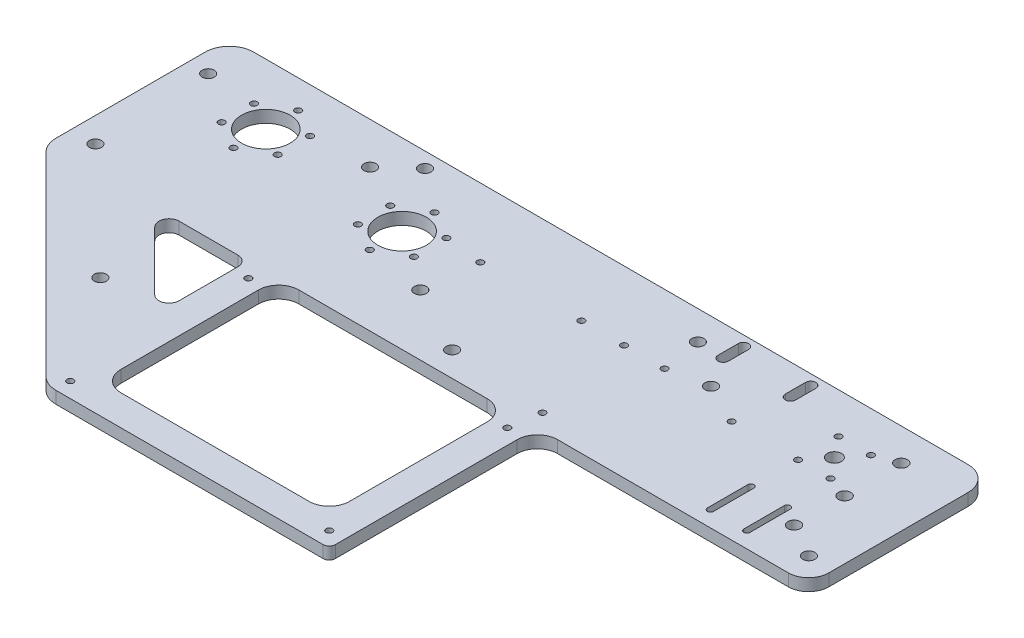
SolidWorks part; units mm, degrees
material "Policarbonato"
ref_plane "Plano frontal" through (0, 0, 0) normal (0, 0, 1) x (1, 0, 0)
ref_plane "Plano superior" through (0, 0, 0) normal (0, 1, 0) x (1, 0, 0)
ref_plane "Plano direito" through (0, 0, 0) normal (1, 0, 0) x (0, 0, -1)
sketch "Esboço1" plane through (0, 0, 0) normal (0, 1, 0) x (1, 0, 0)
  line L3 (-80.5574, -153.6487) -> (51.4721, -153.6487)
  line L4 (54.4721, -150.6487) -> (54.4721, -60.7886)
  line L6 (188.5279, -40.7886) -> (188.5279, 28)
  line L7 (176.5279, 40) -> (-176.5279, 40)
  line L8 (-188.5279, 28) -> (-188.5279, -45.6781)
  line L12 (-122.5768, -50.7886) -> (-93.5279, -50.7886)
  line L13 (-88.5279, -55.7886) -> (-88.5279, -84.8375)
  line L14 (-97.0635, -88.373) -> (-126.1124, -59.3241)
  line L15 (39.4721, -60.6487) -> (39.4721, -128.6487)
  line L16 (29.4721, -138.6487) -> (-63.5279, -138.6487)
  line L17 (-73.5279, -128.6487) -> (-73.5279, -60.6487)
  line L18 (-63.5279, -50.6487) -> (29.4721, -50.6487)
  line L20 (132.5279, 0) -> (148.5279, 0) construction
  line L21 (132.5279, 0) -> (132.5279, 20) construction
  line L22 (132.5279, 20) -> (148.5279, 20) construction
  line L23 (148.5279, 0) -> (148.5279, 20) construction
  line L24 (132.5279, 0) -> (148.5279, 20) construction
  line L25 (132.5279, 20) -> (148.5279, 0) construction
  line L30 (64.4721, -50.7886) -> (178.5279, -50.7886)
  line L31 (150.2221, -43) -> (150.2221, -23) construction
  line L32 (148.7221, -43) -> (148.7221, -23)
  line L33 (151.7221, -43) -> (151.7221, -23)
  line L34 (141.2221, -45.2211) -> (141.2221, -21.4375) construction
  line L36 (132.2221, -43) -> (132.2221, -23) construction
  line L37 (133.7221, -43) -> (133.7221, -23)
  line L38 (130.7221, -43) -> (130.7221, -23)
  line L39 (49.2221, -43) -> (150.2221, -43) construction
  line L40 (54.4721, -120.5) -> (144.9721, -120.5) construction
  line L41 (54.4721, -120.5) -> (54.4721, -7) construction
  line L42 (54.4721, -7) -> (144.9721, -7) construction
  line L43 (144.9721, -120.5) -> (144.9721, -7) construction
  line L44 (54.4721, -120.5) -> (144.9721, -7) construction
  line L45 (54.4721, -7) -> (144.9721, -120.5) construction
  line L46 (70.5279, 25) -> (70.5279, 35) construction
  line L47 (67.9779, 25) -> (67.9779, 35)
  line L48 (73.0779, 25) -> (73.0779, 35)
  line L49 (103.7779, 25) -> (103.7779, 35) construction
  line L50 (101.2279, 25) -> (101.2279, 35)
  line L51 (106.3279, 25) -> (106.3279, 35)
  line L52 (-185.0132, -54.1634) -> (-89.0426, -150.134)
  circle A0 centre (-81.0279, -58.1487) radius 1.6
  circle A1 centre (-81.0279, -146.1487) radius 1.6
  circle A2 centre (46.9721, -58.1487) radius 1.6
  circle A3 centre (46.9721, -146.1487) radius 1.6
  circle A8 centre (176.311, -38.4318) radius 3
  circle A9 centre (0, -38.4318) radius 3
  circle A11 centre (-140.5279, 10) radius 12
  circle A20 centre (-140.5279, 10) radius 16 construction
  circle A21 centre (-140.5279, -6) radius 1.6
  circle A22 centre (-154.3843, 2) radius 1.6
  circle A23 centre (-154.3843, 18) radius 1.6
  circle A24 centre (-84.3674, 32.5) radius 3
  circle A25 centre (-176.311, -38.4318) radius 3
  circle A26 centre (140.5279, 10) radius 3.5
  circle A27 centre (148.5279, 0) radius 1.6
  circle A28 centre (148.5279, 20) radius 1.6
  circle A29 centre (132.5279, 0) radius 1.6
  circle A30 centre (132.5279, 20) radius 1.6
  arc A31 (51.4721, -153.6487) -> (54.4721, -150.6487) centre (51.4721, -150.6487) ccw
  arc A34 (188.5279, 28) -> (176.5279, 40) centre (176.5279, 28) ccw
  arc A35 (-176.5279, 40) -> (-188.5279, 28) centre (-176.5279, 28) ccw
  arc A39 (-93.5279, -50.7886) -> (-88.5279, -55.7886) centre (-93.5279, -55.7886) cw
  arc A40 (-88.5279, -84.8375) -> (-97.0635, -88.373) centre (-93.5279, -84.8375) cw
  arc A41 (-126.1124, -59.3241) -> (-122.5768, -50.7886) centre (-122.5768, -55.7886) cw
  arc A42 (39.4721, -128.6487) -> (29.4721, -138.6487) centre (29.4721, -128.6487) cw
  arc A43 (-63.5279, -138.6487) -> (-73.5279, -128.6487) centre (-63.5279, -128.6487) cw
  arc A44 (-73.5279, -60.6487) -> (-63.5279, -50.6487) centre (-63.5279, -60.6487) cw
  arc A45 (29.4721, -50.6487) -> (39.4721, -60.6487) centre (29.4721, -60.6487) cw
  circle A46 centre (-140.5279, 26) radius 1.6
  circle A47 centre (-126.6715, 18) radius 1.6
  circle A48 centre (-126.6715, 2) radius 1.6
  circle A49 centre (-63.1716, 0) radius 16 construction
  circle A50 centre (-63.1716, -16) radius 1.6
  circle A51 centre (-77.028, -8) radius 1.6
  circle A52 centre (-77.028, 8) radius 1.6
  circle A53 centre (-63.1716, 16) radius 1.6
  circle A54 centre (-49.3152, 8) radius 1.6
  circle A55 centre (-49.3152, -8) radius 1.6
  circle A56 centre (-63.1716, 0) radius 12
  circle A57 centre (-33.5279, -20.6487) radius 3
  circle A58 centre (79.5279, 10) radius 3
  arc A62 (188.5279, -40.7886) -> (178.5279, -50.7886) centre (178.5279, -40.7886) cw
  arc A63 (54.4721, -60.7886) -> (64.4721, -50.7886) centre (64.4721, -60.7886) cw
  arc A64 (148.7221, -43) -> (151.7221, -43) centre (150.2221, -43) ccw
  arc A65 (151.7221, -23) -> (148.7221, -23) centre (150.2221, -23) ccw
  arc A66 (133.7221, -43) -> (130.7221, -43) centre (132.2221, -43) cw
  arc A67 (130.7221, -23) -> (133.7221, -23) centre (132.2221, -23) cw
  circle A68 centre (99.7221, 0) radius 1.6
  circle A69 centre (49.2221, -43) radius 1.6
  circle A70 centre (150.2221, -43) radius 1.6 construction
  circle A71 centre (-30.5279, 6) radius 1.6
  circle A72 centre (19.4721, 6) radius 1.6
  circle A73 centre (60.5279, 6) radius 1.6
  circle A75 centre (40.5279, 6) radius 1.6
  circle A76 centre (70.5279, 30) radius 2.55 construction
  circle A77 centre (103.7779, 30) radius 2.55 construction
  circle A78 centre (159.4679, 24.07) radius 3.05
  circle A79 centre (159.4679, -3.93) radius 3.05
  circle A80 centre (159.4679, -28.93) radius 3.05
  arc A81 (67.9779, 25) -> (73.0779, 25) centre (70.5279, 25) ccw
  arc A82 (73.0779, 35) -> (67.9779, 35) centre (70.5279, 35) ccw
  arc A83 (101.2279, 25) -> (106.3279, 25) centre (103.7779, 25) ccw
  arc A84 (106.3279, 35) -> (101.2279, 35) centre (103.7779, 35) ccw
  circle A85 centre (-178.5279, 19.5) radius 3
  circle A86 centre (-98.5279, 19.5) radius 3
  arc A87 (-80.5574, -153.6487) -> (-89.0426, -150.134) centre (-80.5574, -141.6487) cw
  arc A88 (-185.0132, -54.1634) -> (-188.5279, -45.6781) centre (-176.5279, -45.6781) cw
  circle A89 centre (57.3279, 25.68) radius 3
  point P14 (150.2221, -33)
  point P43 (-140.5279, 10)
  point P70 (-144.4721, -50.6487)
  point P82 (-85.5279, -153.6487)
  point P116 (-63.1716, 0)
  point P123 (0, 40)
  point P124 (132.2221, -33)
  point P129 (99.7221, -63.75)
  point P135 (99.7221, -7)
  point P141 (99.7221, -43)
  point P161 (70.5279, 30)
  point P168 (103.7779, 30)
  dimension "D2" = 3
  dimension "D8" = 12
  dimension "D10" = 12
  dimension "D11" = 61
  dimension "D12" = 203.9448
  dimension "D13" = 7.5
  dimension "D14" = 104.1605
  dimension "D16" = 135.7229
  dimension "D20" = 19.68
  dimension "D21" = 3.2
  dimension "D22" = 48.4318
  dimension "D23" = 32
  dimension "D24" = 3.2
  dimension "D25" = 6
  dimension "D26" = 24
  dimension "D27" = 48
  dimension "D28" = 30
  dimension "D29" = 40
  dimension "D30" = 6
  dimension "D34" = 30
  dimension "D31" = 32
  dimension "D32" = 3.2
  dimension "D33" = 24
  dimension "D35" = 6
  dimension "D36" = 155
  dimension "D37" = 30
  dimension "D44" = 7
  dimension "D48" = 10
  dimension "D6" = 10
  dimension "D58" = 5
  dimension "D62" = 1.5
  dimension "D68" = 101
  dimension "D72" = 80
  dimension "D75" = 5.1
  dimension "D80" = 14.07
  dimension "D82" = 6.1
  dimension "D83" = 10
  dimension "D19" = 6
  dimension "D1" = 137
  dimension "D9" = 377.0558
  dimension "D15" = 225
  dimension "D17" = 38
  dimension "D18" = 15
  dimension "D38" = 48
  dimension "D39" = 15
  dimension "D40" = 12.2169
  dimension "D41" = 12.2169
  dimension "D42" = 16
  dimension "D43" = 20
  dimension "D45" = 15
  dimension "D46" = 15
  dimension "D49" = 7.5
  dimension "D50" = 7.5
  dimension "D51" = 88
  dimension "D52" = 128
  dimension "D53" = 93
  dimension "D56" = 20.6487
  dimension "D57" = 68
  dimension "D59" = 10
  dimension "D60" = 20.5
  dimension "D61" = 20
  dimension "D63" = 9
  dimension "D64" = 113.5
  dimension "D65" = 90.5
  dimension "D66" = 7
  dimension "D67" = 43
  dimension "D69" = 34
  dimension "D70" = 110
  dimension "D71" = 50
  dimension "D73" = 20
  dimension "D74" = 33.25
  dimension "D76" = 10
  dimension "D77" = 10
  dimension "D78" = 25
  dimension "D79" = 28
  dimension "D81" = 18.94
  dimension "D84" = 80
extrude "Ressalto-extrusão1" add sketch "Esboço1" against normal blind 6
sketch "Esboço2" plane through (0, 0, 0) normal (0, 1, 0) x (1, 0, 0)
  line L1 (-126.1124, -59.3241) -> (-97.0635, -88.373) construction
  line L2 (-131.2731, -107.9035) -> (-104.403, -81.0335) construction
  line L3 (-185.0132, -54.1634) -> (-89.0426, -150.134) construction
  circle A1 centre (-117.8381, -94.4685) radius 3
  arc A2 (-188.5279, -45.6781) -> (-185.0132, -54.1634) centre (-176.5279, -45.6781) ccw construction
  point P1 (-117.8381, -94.4685)
  dimension "D1" = 76
  dimension "D2" = 6
extrude "Corte-extrusão1" cut sketch "Esboço2" against normal blind 10
